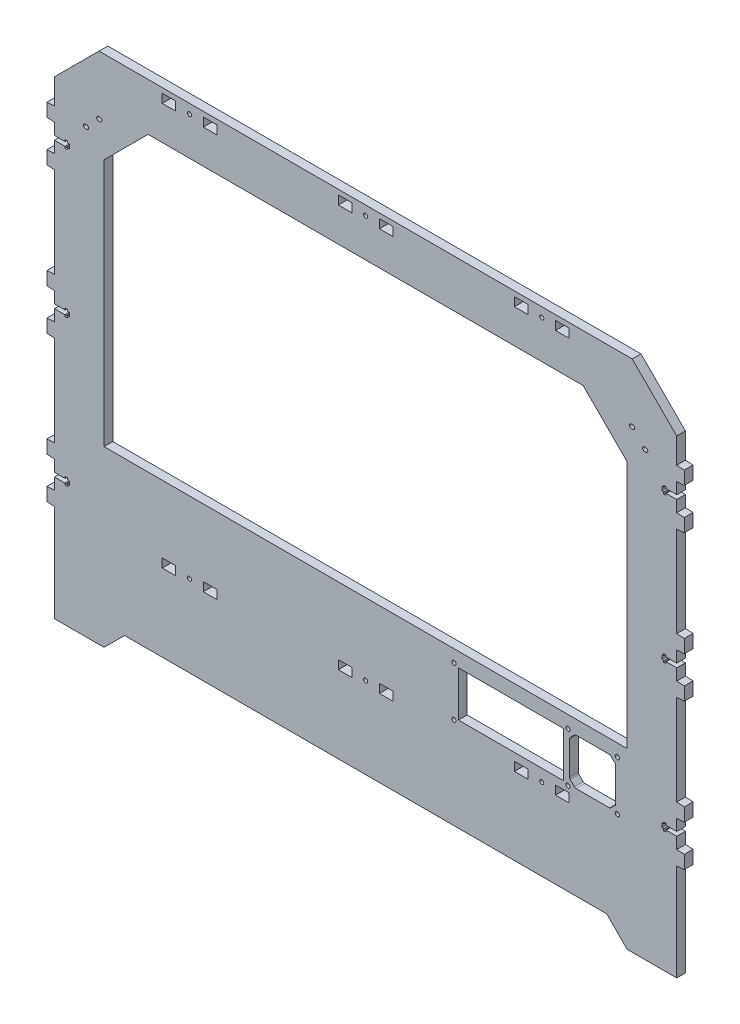
SolidWorks part; units mm, degrees
ref_plane "Front Plane" through (0, 0, 0) normal (0, 0, 1) x (1, 0, 0)
ref_plane "Top Plane" through (0, 0, 0) normal (0, 1, 0) x (1, 0, 0)
ref_plane "Right Plane" through (0, 0, 0) normal (1, 0, 0) x (0, 0, -1)
sketch "Sketch1" plane through (0, 0, 0) normal (0, 0, 1) x (1, 0, 0)
  line L0 (134.7234, -246.5755) -> (134.7234, -252.9755) construction
  line L1 (-74.7828, 50.6245) -> (314.2269, 50.6245)
  line L2 (104.7221, -246.5755) -> (104.7221, -252.9755) construction
  line L3 (278.4439, 15.8745) -> (-38.9998, 15.8745)
  line L4 (346.7221, -0.3499) -> (346.7221, 18.1293)
  line L5 (99.8221, -252.9755) -> (109.6221, -252.9755)
  line L6 (129.8234, -252.9755) -> (129.8234, -246.5755)
  line L7 (99.8221, -246.5755) -> (109.6221, -246.5755)
  line L8 (139.6234, -252.9755) -> (139.6234, -246.5755)
  line L9 (109.6221, -249.7755) -> (129.8234, -249.7755) construction
  line L10 (99.8221, -252.9755) -> (99.8221, -246.5755)
  line L11 (310.5721, -16.2537) -> (310.5721, -197.4755)
  line L12 (1.3234, -252.9755) -> (1.3234, -246.5755)
  line L13 (11.1234, -246.5755) -> (1.3234, -246.5755)
  line L14 (11.1234, -252.9755) -> (11.1234, -246.5755)
  line L15 (11.1234, -252.9755) -> (1.3234, -252.9755)
  line L16 (346.7221, -266.7155) -> (346.7221, -304.3255)
  line L17 (-107.2779, -253.3999) -> (-107.2779, -324.3255)
  line L18 (109.6221, -252.9755) -> (109.6221, -246.5755)
  line L19 (139.6234, -246.5755) -> (129.8234, -246.5755)
  line L20 (139.6234, -252.9755) -> (129.8234, -252.9755)
  line L21 (263.2234, -246.5755) -> (263.2234, -252.9755) construction
  line L22 (233.2221, -246.5755) -> (233.2221, -252.9755) construction
  line L23 (228.3221, -252.9755) -> (238.1221, -252.9755)
  line L24 (258.3234, -252.9755) -> (258.3234, -246.5755)
  line L25 (228.3221, -246.5755) -> (238.1221, -246.5755)
  line L26 (268.1234, -252.9755) -> (268.1234, -246.5755)
  line L27 (238.1221, -249.7755) -> (258.3234, -249.7755) construction
  line L28 (228.3221, -252.9755) -> (228.3221, -246.5755)
  line L29 (238.1221, -252.9755) -> (238.1221, -246.5755)
  line L30 (268.1234, -246.5755) -> (258.3234, -246.5755)
  line L31 (268.1234, -252.9755) -> (258.3234, -252.9755)
  line L32 (-74.7828, 50.6245) -> (-107.2779, 18.1293)
  line L33 (263.2234, 47.0245) -> (263.2234, 40.6245) construction
  line L34 (233.2221, 47.0245) -> (233.2221, 40.6245) construction
  line L35 (228.3221, 40.6245) -> (238.1221, 40.6245)
  line L36 (258.3234, 40.6245) -> (258.3234, 47.0245)
  line L37 (228.3221, 47.0245) -> (238.1221, 47.0245)
  line L38 (268.1234, 40.6245) -> (268.1234, 47.0245)
  line L39 (238.1221, 43.8245) -> (258.3234, 43.8245) construction
  line L40 (228.3221, 40.6245) -> (228.3221, 47.0245)
  line L41 (238.1221, 40.6245) -> (238.1221, 47.0245)
  line L42 (268.1234, 47.0245) -> (258.3234, 47.0245)
  line L43 (268.1234, 40.6245) -> (258.3234, 40.6245)
  line L44 (134.7234, 47.0245) -> (134.7234, 40.6245) construction
  line L45 (104.7221, 47.0245) -> (104.7221, 40.6245) construction
  line L46 (99.8221, 40.6245) -> (109.6221, 40.6245)
  line L47 (129.8234, 40.6245) -> (129.8234, 47.0245)
  line L48 (99.8221, 47.0245) -> (109.6221, 47.0245)
  line L49 (139.6234, 40.6245) -> (139.6234, 47.0245)
  line L50 (109.6221, 43.8245) -> (129.8234, 43.8245) construction
  line L51 (99.8221, 40.6245) -> (99.8221, 47.0245)
  line L52 (-71.1279, -16.2537) -> (-71.1279, -197.4755)
  line L53 (324.0971, -0.4255) -> (323.2971, -0.4255)
  line L54 (-71.1279, -197.4755) -> (310.5721, -197.4755)
  line L55 (-75.0529, 6.1745) -> (-74.2529, 6.1745)
  line L56 (-107.2779, -40.5999) -> (-107.2779, -106.7499)
  line L57 (109.6221, 40.6245) -> (109.6221, 47.0245)
  line L58 (-107.2779, -213.1499) -> (-107.2779, -146.9999)
  line L59 (-107.2779, -324.3255) -> (-107.3256, -324.061)
  line L60 (-38.9998, 15.8745) -> (-71.1279, -16.2537)
  line L61 (-107.2779, 18.1293) -> (-107.2779, -0.3499)
  line L62 (346.7221, -40.5999) -> (346.7221, -106.7499)
  line L63 (346.7221, -125.3749) -> (346.7221, -116.9999)
  line L64 (-107.2779, -0.3499) -> (-107.1734, -0.2377)
  line L65 (346.7221, -146.9999) -> (346.7221, -213.1499)
  line L66 (139.6234, 47.0245) -> (129.8234, 47.0245)
  line L67 (139.6234, 40.6245) -> (129.8234, 40.6245)
  line L68 (-99.5779, -21.9762) -> (-107.2779, -21.9762)
  line L69 (-107.2779, -21.9762) -> (-107.2779, -30.1749)
  line L70 (-97.7779, -23.2249) -> (-97.7779, -21.9762)
  line L71 (-112.7779, -40.3249) -> (-107.2779, -40.5999)
  line L72 (-96.3779, -21.9762) -> (-97.7779, -21.9762)
  line L73 (-107.2779, -10.7749) -> (-107.2779, -18.9749)
  line L74 (-97.7779, -18.9749) -> (-97.7779, -17.7249)
  line L75 (-107.2779, -18.9749) -> (-107.2779, -10.7749)
  line L76 (-112.7779, -30.6249) -> (-107.2779, -30.3499)
  line L77 (-97.7779, -17.7249) -> (-99.5779, -17.7249)
  line L78 (-96.3779, -18.9749) -> (-97.7779, -18.9749)
  line L79 (6.2234, 47.0245) -> (6.2234, 40.6245) construction
  line L80 (-99.5779, -18.9749) -> (-107.2779, -18.9749)
  line L81 (-99.5779, -17.7249) -> (-99.5779, -18.9749)
  line L82 (-99.5779, -23.2249) -> (-99.5779, -21.9762)
  line L83 (-97.7779, -23.2249) -> (-99.5779, -23.2249)
  line L84 (-96.3779, -18.9749) -> (-96.3779, -21.9762)
  line L85 (-107.2779, -10.7749) -> (-107.2779, -18.9749)
  line L86 (-107.2779, -10.7749) -> (-107.2779, -18.9749)
  line L87 (-107.2779, -21.9762) -> (-107.2779, -30.1749)
  line L88 (-23.7779, 47.0245) -> (-23.7779, 40.6245) construction
  line L89 (-84.6529, -0.4255) -> (-83.8529, -0.4255)
  line L90 (-28.6779, 40.6245) -> (-18.8779, 40.6245)
  line L91 (-112.7779, -0.6249) -> (-107.2779, -0.3499)
  line L92 (-97.7779, -125.3749) -> (-97.7779, -124.1249)
  line L93 (-96.3779, -125.3749) -> (-97.7779, -125.3749)
  line L94 (-99.5779, -124.1249) -> (-99.5779, -125.3749)
  line L95 (-96.3779, -125.3749) -> (-96.3779, -128.3762)
  line L96 (-99.5779, -129.6249) -> (-99.5779, -128.3762)
  line L97 (-107.2779, -18.9749) -> (-107.2779, -10.7749)
  line L98 (-96.3779, -128.3762) -> (-97.7779, -128.3762)
  line L99 (-99.5779, -125.3749) -> (-107.2779, -125.3749)
  line L100 (-97.7779, -129.6249) -> (-99.5779, -129.6249)
  line L101 (-99.5779, -128.3762) -> (-107.2779, -128.3762)
  line L102 (-28.6779, -252.9755) -> (-18.8779, -252.9755)
  line L103 (-28.6779, -252.9755) -> (-28.6779, -246.5755)
  line L104 (-28.6779, -246.5755) -> (-18.8779, -246.5755)
  line L105 (-18.8779, -252.9755) -> (-18.8779, -246.5755)
  line L106 (-107.2779, -125.3749) -> (-107.2779, -117.1749)
  line L107 (-112.7779, -10.3249) -> (-107.2779, -10.5999)
  line L108 (-107.2779, -30.1749) -> (-107.2779, -30.3499)
  line L109 (-107.2779, -128.3762) -> (-107.2779, -136.5749)
  line L110 (-97.7779, -124.1249) -> (-99.5779, -124.1249)
  line L111 (-112.7779, -40.3249) -> (-112.7779, -30.6249)
  line L112 (-107.2779, -128.3762) -> (-107.2779, -136.5749)
  line L113 (-97.7779, -129.6249) -> (-97.7779, -128.3762)
  line L114 (-107.2779, -21.9762) -> (-107.2779, -30.1749)
  line L115 (-107.2779, -117.1749) -> (-107.2779, -125.3749)
  line L116 (-107.2779, -117.1749) -> (-107.2779, -125.3749)
  line L117 (-112.7779, -10.3249) -> (-112.7779, -0.6249)
  line L118 (-107.2779, -223.5749) -> (-107.2779, -231.7749)
  line L119 (-97.7779, -231.7749) -> (-97.7779, -230.5249)
  line L120 (-96.3779, -231.7749) -> (-97.7779, -231.7749)
  line L121 (-107.2779, -10.5999) -> (-107.2779, -10.7749)
  line L122 (1.3234, 40.6245) -> (1.3234, 47.0245)
  line L123 (-99.5779, -230.5249) -> (-99.5779, -231.7749)
  line L124 (-96.3779, -231.7749) -> (-96.3779, -234.7762)
  line L125 (-28.6779, 47.0245) -> (-18.8779, 47.0245)
  line L126 (-99.5779, -236.0249) -> (-99.5779, -234.7762)
  line L127 (-96.3779, -234.7762) -> (-97.7779, -234.7762)
  line L128 (-107.2779, -231.7749) -> (-107.2779, -223.5749)
  line L129 (-107.2779, -234.7762) -> (-107.2779, -242.9749)
  line L130 (-99.5779, -231.7749) -> (-107.2779, -231.7749)
  line L131 (-112.7779, -146.7249) -> (-107.2779, -146.9999)
  line L132 (-97.7779, -236.0249) -> (-99.5779, -236.0249)
  line L133 (-99.5779, -234.7762) -> (-107.2779, -234.7762)
  line L134 (-97.7779, -230.5249) -> (-99.5779, -230.5249)
  line L135 (-107.2779, -223.5749) -> (-107.2779, -231.7749)
  line L136 (11.1234, 40.6245) -> (11.1234, 47.0245)
  line L137 (-18.8779, 43.8245) -> (1.3234, 43.8245) construction
  line L138 (-28.6779, 40.6245) -> (-28.6779, 47.0245)
  line L139 (-97.7779, -236.0249) -> (-97.7779, -234.7762)
  line L140 (-107.2779, -234.7762) -> (-107.2779, -242.9749)
  line L141 (346.7221, -257.9755) -> (346.7221, -253.3999)
  line L142 (346.7221, -21.9762) -> (346.7221, -30.1749)
  line L143 (346.7221, -10.7749) -> (346.7221, -18.9749)
  line L144 (346.7221, -234.7749) -> (346.7221, -243.1499)
  line L145 (339.0221, -129.6249) -> (339.0221, -128.3762)
  line L146 (346.7221, -223.3999) -> (346.7232, -231.7735)
  line L147 (335.8221, -125.3749) -> (337.2221, -125.3749)
  line L148 (335.8221, -128.3762) -> (337.2221, -128.3762)
  line L149 (346.7221, -10.7749) -> (346.7221, -18.9749)
  line L150 (335.8221, -125.3749) -> (335.8221, -128.3762)
  line L151 (-18.8779, 40.6245) -> (-18.8779, 47.0245)
  line L152 (339.0221, -125.3749) -> (346.7221, -125.3749)
  line L153 (11.1234, 47.0245) -> (1.3234, 47.0245)
  line L154 (11.1234, 40.6245) -> (1.3234, 40.6245)
  line L155 (337.2221, -125.3749) -> (337.2221, -124.1249)
  line L156 (337.2221, -129.6249) -> (339.0221, -129.6249)
  line L157 (352.2221, -116.7249) -> (346.7221, -116.9999)
  line L158 (339.0221, -128.3762) -> (346.7221, -128.3762)
  line L159 (346.7221, -136.5749) -> (346.7221, -136.7499)
  line L160 (339.0221, -124.1249) -> (339.0221, -125.3749)
  line L162 (352.2221, -116.7249) -> (352.2221, -107.0249)
  line L163 (337.2221, -124.1249) -> (339.0221, -124.1249)
  line L165 (335.8221, -18.9749) -> (335.8221, -21.9762)
  line L166 (-18.8779, -249.7755) -> (1.3234, -249.7755) construction
  line L170 (337.2221, -23.2249) -> (339.0221, -23.2249)
  line L171 (339.0221, -23.2249) -> (339.0221, -21.9762)
  line L172 (339.0221, -17.7249) -> (339.0221, -18.9749)
  line L173 (339.0221, -18.9749) -> (346.7232, -18.9749)
  line L174 (346.7221, -10.7749) -> (346.7221, -18.9749)
  line L175 (335.8221, -18.9749) -> (337.2221, -18.9749)
  line L176 (337.2221, -17.7249) -> (339.0221, -17.7249)
  line L177 (314.2269, 50.6245) -> (346.7221, 18.1293)
  line L178 (346.7221, -18.9749) -> (346.7221, -10.7749)
  line L179 (337.2221, -18.9749) -> (337.2221, -17.7249)
  line L180 (346.7221, -18.9749) -> (346.7221, -10.7749)
  line L181 (335.8221, -21.9762) -> (337.2221, -21.9762)
  line L182 (346.7221, -21.9762) -> (346.7221, -30.1749)
  line L183 (337.2221, -23.2249) -> (337.2221, -21.9762)
  line L184 (346.7221, -21.9762) -> (346.7221, -30.1749)
  line L185 (339.0221, -21.9762) -> (346.7221, -21.9762)
  line L188 (352.2221, -107.0249) -> (346.7221, -106.7499)
  line L189 (337.2221, -129.6249) -> (337.2221, -128.3762)
  line L190 (346.7221, -128.3762) -> (346.7221, -136.5749)
  line L191 (346.7221, -128.3762) -> (346.7221, -136.5749)
  line L192 (339.0221, -236.0235) -> (339.0221, -234.7749)
  line L193 (346.7221, -128.3762) -> (346.7221, -136.5749)
  line L195 (352.2221, -137.0249) -> (346.7221, -136.7499)
  line L197 (335.8221, -231.7735) -> (337.2221, -231.7735)
  line L198 (335.8221, -234.7749) -> (337.2221, -234.7749)
  line L199 (335.8221, -231.7735) -> (335.8221, -234.7749)
  line L200 (339.0221, -231.7735) -> (346.7232, -231.7735)
  line L201 (352.2221, -146.7249) -> (352.2221, -137.0249)
  line L202 (337.2221, -231.7735) -> (337.2221, -230.5235)
  line L203 (337.2221, -236.0235) -> (339.0221, -236.0235)
  line L204 (339.0221, -234.7749) -> (346.7221, -234.7749)
  line L205 (339.0221, -230.5235) -> (339.0221, -231.7735)
  line L206 (337.2221, -230.5235) -> (339.0221, -230.5235)
  line L209 (278.4439, 15.8745) -> (310.5721, -16.2537)
  line L210 (-107.2779, -324.3255) -> (-71.1279, -324.3255)
  line L211 (-75.0529, 9.1745) -> (-74.2529, 9.1745)
  line L212 (-71.1279, -324.3255) -> (-56.1298, -309.3274)
  line L213 (184.1621, -206.4755) -> (184.1621, -242.4755) construction
  line L214 (323.2971, -0.4255) -> (323.2971, -1.9255) construction
  line L215 (346.7221, -257.9755) -> (346.7221, -266.7155)
  line L216 (-84.6529, -3.4255) -> (-83.8529, -3.4255)
  line L217 (-84.6529, 7.6745) -> (-84.6529, -1.9255) construction
  line L219 (-84.6529, -0.4573) -> (-75.0529, 7.6745) construction
  line L220 (-84.6529, 7.6745) -> (-75.0529, 7.6745) construction
  line L222 (324.0971, 7.6745) -> (324.0971, -1.9255) construction
  line L223 (324.0971, 7.6745) -> (314.4971, 7.6745) construction
  line L228 (323.2971, -3.4255) -> (324.0971, -3.4255)
  line L230 (314.4971, 9.1745) -> (313.6971, 9.1745)
  line L231 (313.6971, 9.1745) -> (313.6971, 7.6745) construction
  line L232 (267.3621, -206.4755) -> (303.3621, -206.4755) construction
  line L233 (267.3621, -206.4755) -> (267.3621, -242.4755) construction
  line L235 (297.4582, -207.6129) -> (273.2666, -207.6129)
  line L237 (272.0291, -208.1255) -> (269.0125, -211.1421)
  line L241 (-107.2779, -117.1749) -> (-107.2779, -125.3749)
  line L243 (267.3621, -242.4755) -> (303.3621, -242.4755) construction
  line L244 (268.4999, -212.3796) -> (268.4999, -236.5712)
  line L245 (303.3621, -206.4755) -> (303.3621, -242.4755) construction
  line L246 (313.6971, 6.1745) -> (314.4971, 6.1745)
  line L249 (301.7124, -211.1421) -> (298.6957, -208.1255)
  line L252 (337.2221, -236.0235) -> (337.2221, -234.7749)
  line L253 (264.0621, -240.9755) -> (187.4621, -240.9755)
  line L254 (264.0621, -240.9755) -> (264.0621, -207.9755)
  line L255 (264.0621, -207.9755) -> (187.4621, -207.9755)
  line L256 (187.4621, -240.9755) -> (187.4621, -207.9755)
  line L258 (346.7221, -324.3255) -> (310.5721, -324.3255)
  line L259 (302.2249, -236.5712) -> (302.2249, -212.3796)
  line L260 (310.5721, -324.3255) -> (295.5739, -309.3274)
  line L261 (-56.1298, -309.3274) -> (295.5739, -309.3274)
  line L262 (346.7221, -324.3255) -> (346.7221, -304.3255)
  line L263 (-23.7779, -246.5755) -> (-23.7779, -252.9755) construction
  line L265 (6.2234, -246.5755) -> (6.2234, -252.9755) construction
  line L267 (352.2221, -30.6249) -> (346.7221, -30.3499)
  line L268 (352.2221, -10.3249) -> (346.7221, -10.5999)
  line L271 (346.7221, -21.9749) -> (346.7221, -30.1749)
  line L272 (352.2221, -10.3249) -> (352.2221, -0.6249)
  line L273 (346.7221, -30.1749) -> (346.7221, -21.9749)
  line L274 (346.7221, -18.9735) -> (346.7232, -18.9749)
  line L275 (346.7221, -10.7749) -> (346.7221, -10.5999)
  line L277 (352.2221, -40.3249) -> (346.7221, -40.5999)
  line L278 (346.7221, -30.1749) -> (346.7221, -21.9749)
  line L280 (352.2221, -0.6249) -> (346.7221, -0.3499)
  line L281 (346.7221, -18.9735) -> (346.7221, -10.7749)
  line L282 (346.7221, -18.9735) -> (346.7221, -10.7749)
  line L306 (352.2221, -40.3249) -> (352.2221, -30.6249)
  line L307 (346.7221, -30.1749) -> (346.7221, -30.3499)
  line L309 (346.7221, -128.3749) -> (346.7221, -136.5749)
  line L311 (346.7221, -136.5749) -> (346.7221, -128.3749)
  line L312 (346.7221, -128.3762) -> (346.7221, -136.5749)
  line L316 (352.2221, -146.7249) -> (346.7221, -146.9999)
  line L317 (346.7221, -136.5749) -> (346.7221, -128.3749)
  line L318 (346.7221, -128.3762) -> (346.7221, -136.5749)
  line L321 (352.2221, -223.1249) -> (346.7221, -223.3999)
  line L324 (352.2221, -223.1249) -> (352.2221, -213.4249)
  line L326 (352.2221, -213.4249) -> (346.7221, -213.1499)
  line L329 (352.2221, -243.4249) -> (346.7221, -243.1499)
  line L330 (352.2221, -253.1249) -> (352.2221, -243.4249)
  line L339 (346.7221, -258.5749) -> (346.7221, -253.3999)
  line L340 (352.2221, -253.1249) -> (346.7221, -253.3999)
  line L344 (-112.7779, -137.0249) -> (-107.2779, -136.7499)
  line L346 (-112.7779, -107.0249) -> (-107.2779, -106.7499)
  line L347 (-107.2779, -125.3749) -> (-107.2779, -117.1749)
  line L348 (-112.7779, -116.7249) -> (-107.2779, -116.9999)
  line L349 (-107.2779, -136.5749) -> (-107.2779, -136.7499)
  line L350 (-112.7779, -146.7249) -> (-112.7779, -137.0249)
  line L351 (-107.2779, -128.3762) -> (-107.2779, -136.5749)
  line L352 (-112.7779, -116.7249) -> (-112.7779, -107.0249)
  line L353 (-107.2779, -116.9999) -> (-107.2779, -117.1749)
  line L356 (-112.7779, -253.1249) -> (-107.2779, -253.3999)
  line L357 (-107.2779, -223.5749) -> (-107.2779, -231.7749)
  line L358 (-112.7779, -243.4249) -> (-107.2779, -243.1499)
  line L360 (-112.7779, -213.4249) -> (-107.2779, -213.1499)
  line L361 (-107.2779, -231.7749) -> (-107.2779, -223.5749)
  line L362 (-112.7779, -223.1249) -> (-107.2779, -223.3999)
  line L363 (-107.2779, -242.9749) -> (-107.2779, -243.1499)
  line L364 (-112.7779, -253.1249) -> (-112.7779, -243.4249)
  line L365 (-107.2779, -234.7762) -> (-107.2779, -242.9749)
  line L366 (-112.7779, -223.1249) -> (-112.7779, -213.4249)
  line L367 (-107.2779, -223.3999) -> (-107.2779, -223.5749)
  line L369 (269.0125, -237.8087) -> (272.0291, -240.8253)
  line L370 (273.2666, -241.3379) -> (297.4582, -241.3379)
  line L372 (298.6957, -240.8253) -> (301.7124, -237.8087)
  circle A0 centre (-8.7773, -249.7755) radius 1.5
  circle A1 centre (119.7227, -249.7755) radius 1.5
  circle A2 centre (248.2227, 43.8245) radius 1.5
  circle A3 centre (248.2227, -249.7755) radius 1.5
  circle A4 centre (119.7227, 43.8245) radius 1.5
  circle A5 centre (-8.7773, 43.8245) radius 1.5
  arc A6 (-84.6529, -0.4255) -> (-84.6529, -3.4255) centre (-84.6529, -1.9255) ccw
  arc A7 (-74.2529, 6.1745) -> (-74.2529, 9.1745) centre (-74.1529, 7.6745) ccw
  circle A8 centre (-84.6529, 7.6745) radius 4.9 construction
  arc A9 (-75.0529, 9.1745) -> (-75.0529, 6.1745) centre (-75.0529, 7.6745) ccw
  arc A10 (-83.8529, -3.4255) -> (-83.8529, -0.4255) centre (-83.8529, -1.9255) ccw
  circle A11 centre (324.0971, 7.6745) radius 4.9 construction
  arc A12 (324.0971, -0.4255) -> (324.0971, -3.4255) centre (324.0971, -1.9255) cw
  arc A13 (314.4971, 9.1745) -> (314.4971, 6.1745) centre (314.4971, 7.6745) cw
  circle A14 centre (267.3621, -206.4755) radius 1.55
  circle A15 centre (303.3621, -206.4755) radius 1.55
  circle A16 centre (303.3621, -242.4755) radius 1.55
  circle A17 centre (267.3621, -242.4755) radius 1.55
  circle A18 centre (184.1621, -206.4755) radius 1.55
  circle A19 centre (184.1621, -242.4755) radius 1.55
  arc A20 (298.6957, -208.1255) -> (297.4582, -207.6129) centre (297.4582, -209.3629) ccw
  arc A21 (273.2666, -207.6129) -> (272.0291, -208.1255) centre (273.2666, -209.3629) ccw
  arc A22 (269.0125, -211.1421) -> (268.4999, -212.3796) centre (270.2499, -212.3796) ccw
  arc A23 (302.2249, -212.3796) -> (301.7124, -211.1421) centre (300.4749, -212.3796) ccw
  arc A24 (302.2249, -212.3796) -> (301.7124, -211.1421) centre (300.4749, -212.3796) ccw
  arc A25 (272.0291, -240.8253) -> (273.2666, -241.3379) centre (273.2666, -239.5879) ccw
  arc A26 (323.2971, -0.4255) -> (323.2971, -3.4255) centre (323.2971, -1.9255) ccw
  arc A27 (313.6971, 9.1745) -> (313.6971, 6.1745) centre (313.6971, 7.6745) ccw
  arc A39 (272.0291, -240.8253) -> (273.2666, -241.3379) centre (273.2666, -239.5879) ccw
  arc A40 (297.4582, -241.3379) -> (298.6957, -240.8253) centre (297.4582, -239.5879) ccw
  arc A41 (301.7124, -237.8087) -> (302.2249, -236.5712) centre (300.4749, -236.5712) ccw
  arc A42 (297.4582, -241.3379) -> (298.6957, -240.8253) centre (297.4582, -239.5879) ccw
  arc A43 (301.7124, -237.8087) -> (302.2249, -236.5712) centre (300.4749, -236.5712) ccw
  arc A44 (268.4999, -236.5712) -> (269.0125, -237.8087) centre (270.2499, -236.5712) ccw
  arc A45 (268.4999, -236.5712) -> (269.0125, -237.8087) centre (270.2499, -236.5712) ccw
  point P0 (215.5094, -214.6553)
  point P66 (119.7221, -199.9755)
  point P234 (119.7221, -222.9755)
  dimension "D3" = 9.6
  dimension "D7" = 9.6
  dimension "D14" = 30.0014
  dimension "D18" = 6.4
  dimension "D19" = 9.8
  dimension "D25" = 9.6
extrude "Boss-Extrude1" add sketch "Sketch1" along normal blind 6.4
